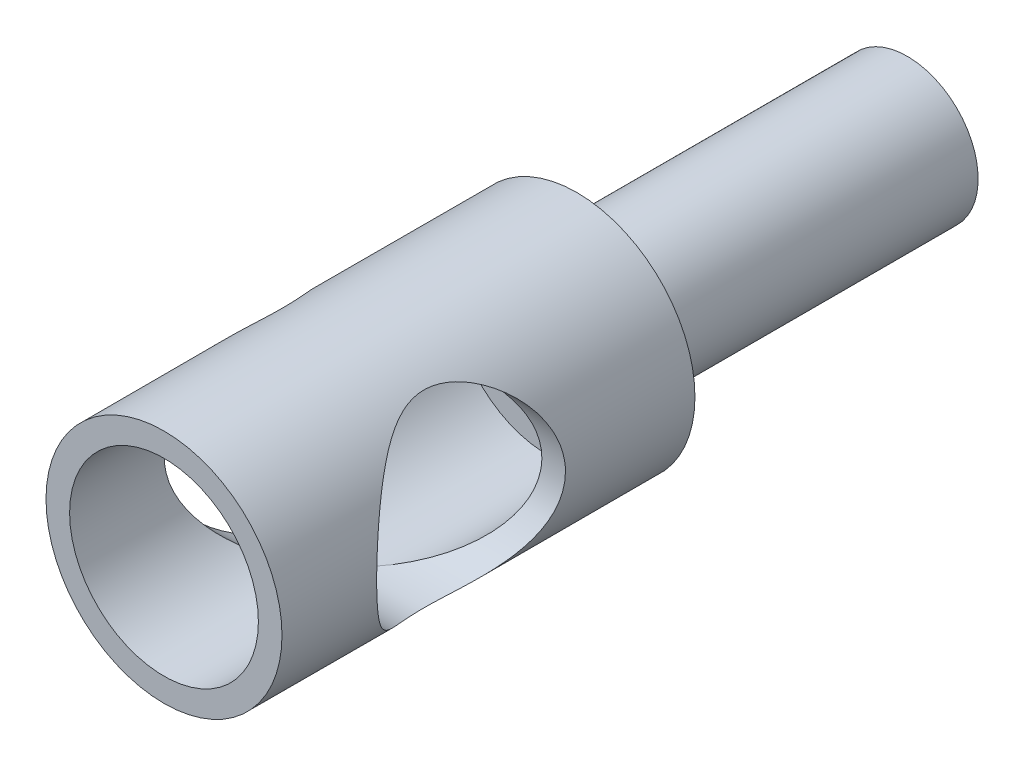
SolidWorks part; units mm, degrees
ref_plane "前视基准面" through (0, 0, 0) normal (0, 0, 1) x (1, 0, 0)
ref_plane "上视基准面" through (0, 0, 0) normal (0, 1, 0) x (1, 0, 0)
ref_plane "右视基准面" through (0, 0, 0) normal (1, 0, 0) x (0, 0, -1)
sketch "草图1" plane through (0, 0, 0) normal (0, 0, 1) x (1, 0, 0)
  circle A0 centre (0, 0) radius 1
  dimension "D1" = 2
extrude "凸台-拉伸1" add sketch "草图1" along normal blind 3.5
sketch "草图3" plane through (0, 0, 0) normal (0, 0, -1) x (-1, 0, 0)
  circle A0 centre (0, 0) radius 0.6
  dimension "D1" = 1.2
extrude "凸台-拉伸2" add sketch "草图3" along normal blind 2.8
sketch "草图4" plane through (0, 0, 0) normal (1, 0, 0) x (0, 0, -1)
  line L0 (0, 1) -> (-3.5, 1) construction
  line L1 (-3.5, 1) -> (-3.5, -1) construction
  circle A0 centre (-1.8974, 0) radius 0.8
  dimension "D1" = 1.6
  dimension "D2" = 1
  dimension "D3" = 1.6026
extrude "切除-拉伸1" cut sketch "草图4" against normal mid plane 2.5
sketch "草图5" plane through (0, 0, 3.5) normal (0, 0, 1) x (1, 0, 0)
  circle A0 centre (0, 0) radius 0.8
  dimension "D1" = 1.6
extrude "切除-拉伸2" cut sketch "草图5" against normal mid plane 6.5
